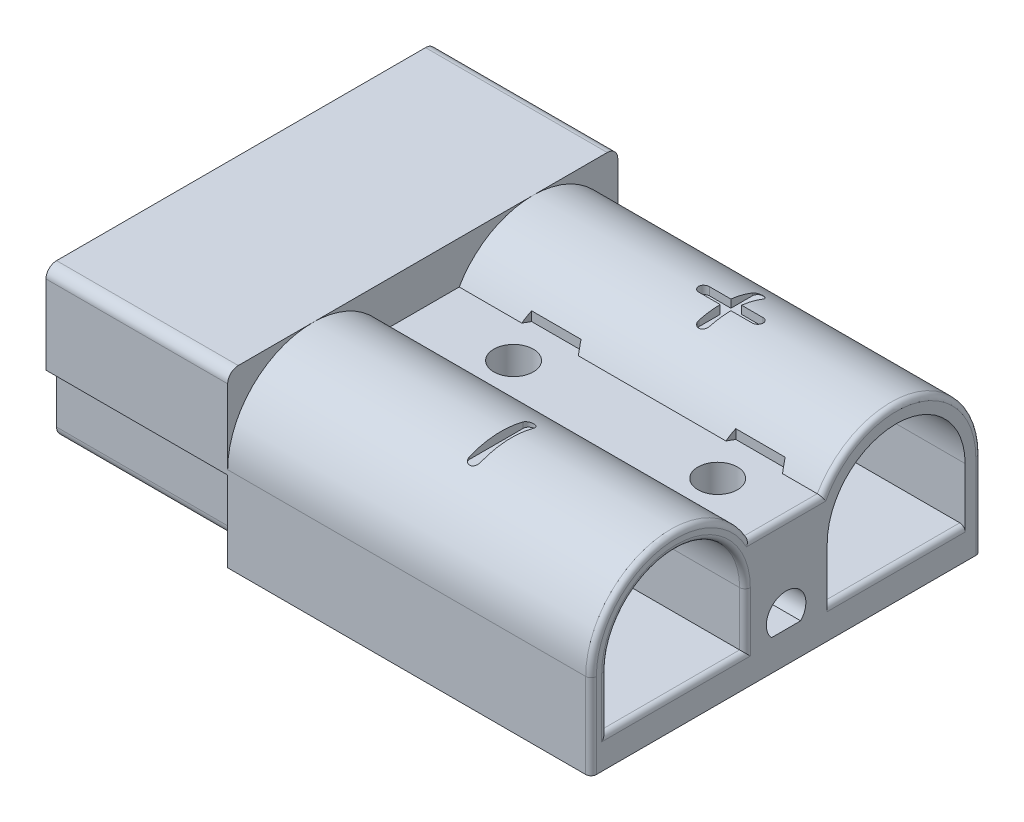
SolidWorks part; units mm, degrees
material "PC High Viscosity"
ref_plane "Front Plane" through (0, 0, 0) normal (0, 0, 1) x (1, 0, 0)
ref_plane "Top Plane" through (0, 0, 0) normal (0, 1, 0) x (1, 0, 0)
ref_plane "Right Plane" through (0, 0, 0) normal (1, 0, 0) x (0, 0, -1)
sketch "Sketch2" plane through (0, 0, 0) normal (1, 0, 0) x (0, 0, -1)
  line L0 (-10.3, -15.3774) -> (-10.3, -26.8774) construction
  line L1 (-18.25, -29.7774) -> (18.25, -29.7774)
  line L2 (-16.75, -21.8274) -> (-16.75, -26.8774)
  line L3 (0, -29.7774) -> (0, -13.8774) construction
  line L4 (10.3, -15.3774) -> (10.3, -26.8774) construction
  line L5 (3.85, -26.8774) -> (16.75, -26.8774)
  line L6 (-1.85, -13.8774) -> (-1.85, -29.7774) construction
  line L7 (1.85, -13.8774) -> (1.85, -29.7774) construction
  line L8 (-18.25, -21.8274) -> (-18.25, -29.7774)
  line L9 (18.25, -21.8274) -> (18.25, -29.7774)
  line L10 (-16.75, -26.8774) -> (-3.85, -26.8774)
  line L12 (-18.25, -21.8274) -> (-2.35, -21.8274) construction
  line L13 (16.75, -21.8274) -> (16.75, -28.2774) construction
  line L14 (2.35, -21.8274) -> (18.25, -21.8274) construction
  line L15 (-3.85, -26.8774) -> (3.85, -26.8774) construction
  line L16 (-3.4151, -17.8524) -> (3.4151, -17.8524)
  line L17 (-16.75, -21.8274) -> (-16.75, -28.2774) construction
  line L18 (-1.3638, -26.8774) -> (1.3638, -26.8774)
  line L22 (16.75, -21.8274) -> (16.75, -26.8774)
  line L32 (-3.85, -21.8274) -> (-3.85, -26.8774)
  line L33 (3.85, -21.8274) -> (3.85, -26.8774)
  line L36 (-16.75, -28.2774) -> (16.75, -28.2774) construction
  line L37 (-18.25, -29.7774) -> (18.25, -29.7774) construction
  arc A0 (-3.4151, -17.8524) -> (-18.25, -21.8274) centre (-10.3, -21.8274) ccw
  arc A1 (1.3638, -26.8774) -> (-1.3638, -26.8774) centre (0, -25.6274) ccw
  arc A5 (18.25, -21.8274) -> (3.4151, -17.8524) centre (10.3, -21.8274) ccw
  arc A7 (-3.85, -21.8274) -> (-16.75, -21.8274) centre (-10.3, -21.8274) ccw
  arc A8 (16.75, -21.8274) -> (3.85, -21.8274) centre (10.3, -21.8274) ccw
  arc A10 (18.25, -21.8274) -> (2.35, -21.8274) centre (10.3, -21.8274) ccw construction
  arc A11 (-2.35, -21.8274) -> (-18.25, -21.8274) centre (-10.3, -21.8274) ccw construction
  point P8 (0.7875, -13.9399)
  point P9 (-3.5, 15.8375)
  point P10 (-31.425, 15.8375)
  point P11 (18.25, -13.8774)
  point P12 (-31.425, -6.5)
  point P13 (0, 15.8375)
  point P15 (10.802, 3)
  point P16 (-3.5, -6.5)
  point P20 (-18.25, -13.8774)
  point P23 (-4.2255, -3.5355)
  point P24 (-2.35, -13.8774)
  point P25 (31.925, 15.8375)
  point P26 (17.4625, 15.8375)
  point P28 (-2.35, -29.7774)
  point P30 (2.35, -29.7774)
  point P43 (2.35, -13.8774)
  dimension "D3" = 1.5
  dimension "D1" = 15.9
  dimension "D2" = 36.5
extrude "Extrude1" add sketch "Sketch2" along normal blind 34
fillet "Fillet9" radius 0.5 10 edges at (34, -24.3524, 16.75) (34, -15.3774, 10.3) (34, -25.8024, -18.25) (34, -25.8024, 18.25) (34, -26.8774, -10.3) (34, -24.3524, 3.85) (34, -26.8774, 10.3) (34, -17.8524, 0) (34, -14.1483, -12.3576) (34, -14.1483, 12.3576)
ref_plane "Plane1" through (29, 0, 0) normal (1, 0, 0) x (0, 0, -1)
sketch "Sketch30" plane through (29, 0, 0) normal (1, 0, 0) x (0, 0, -1)
  line L0 (0, -17.8524) -> (0, -29.7774) construction
  line L1 (-3.4151, -17.8524) -> (3.4151, -17.8524) construction
  line L3 (-18.25, -21.8274) -> (18.25, -21.8274) construction
ref_plane "Plane3" through (29, 0, 0) normal (1, 0, 0) x (0, 0, -1)
ref_plane "Plane4" through (0, 0, 0) normal (0, 0, 1) x (1, 0, 0)
ref_plane "Plane7" through (0, 0, 0) normal (-1, 0, 0) x (0, 0, 1)
sketch "Sketch24" plane through (0, 0, 0) normal (-1, 0, 0) x (0, 0, 1)
  line L0 (0, -29.7774) -> (0, -13.8774) construction
  line L2 (-17.2613, -22.3827) -> (-16.2725, -22.3827) construction
  line L3 (-17.2613, -27.3623) -> (-17.2613, -22.3827)
  line L4 (-0.4944, -14.8661) -> (-17.2613, -14.8661) construction
  line L5 (-17.2613, -22.2591) -> (-17.2613, -22.3827)
  line L6 (0.4944, -18.8211) -> (0.9887, -18.8211) construction
  line L7 (17.2613, -22.2591) -> (18.25, -22.2591)
  line L8 (0.9887, -18.8211) -> (0.9887, -19.8098) construction
  line L9 (17.2613, -27.3623) -> (17.2613, -22.3827)
  line L10 (-0.9887, -18.8211) -> (-0.9887, -19.8098) construction
  line L11 (-16.2725, -23.3714) -> (-16.2725, -22.3827) construction
  line L12 (-0.9887, -24.3602) -> (0.9887, -24.3602) construction
  line L13 (16.2725, -23.3714) -> (16.2725, -22.3827) construction
  line L14 (-17.2613, -22.2591) -> (-17.2613, -14.8661) construction
  line L15 (-16.2725, -28.351) -> (16.2725, -28.351)
  line L16 (0.4944, -14.8661) -> (0.4944, -18.8211) construction
  line L17 (18.25, -22.2591) -> (18.25, -14.8661)
  line L18 (0, -13.8774) -> (0, -22.3827) construction
  line L19 (16.2725, -23.3714) -> (-16.2725, -23.3714) construction
  line L20 (0, -24.8545) -> (0, -29.635) construction
  line L21 (17.2613, -13.8774) -> (-17.2613, -13.8774)
  line L22 (17.2613, -22.3827) -> (16.2725, -22.3827) construction
  line L23 (17.2613, -22.2591) -> (17.2613, -14.8661) construction
  line L24 (-18.25, -22.2591) -> (-17.2613, -22.2591)
  line L25 (-0.9887, -18.8211) -> (-0.4944, -18.8211) construction
  line L26 (16.2725, -22.3827) -> (-16.2725, -22.3827) construction
  line L27 (-0.4944, -14.8661) -> (-0.4944, -18.8211) construction
  line L28 (-18.25, -22.2591) -> (-18.25, -14.8661)
  line L29 (-0.9887, -19.8098) -> (0.9887, -19.8098) construction
  line L30 (-0.9887, -24.3602) -> (-0.9887, -28.3623) construction
  line L31 (1.1944, -14.8661) -> (17.2613, -14.8661) construction
  line L32 (17.2613, -22.2591) -> (17.2613, -22.3827)
  line L34 (0.9887, -24.3602) -> (0.9887, -28.3623) construction
  arc A0 (1.9775, -28.351) -> (0.9887, -27.3623) centre (1.9775, -27.3623) cw construction
  arc A1 (-17.2613, -13.8774) -> (-18.25, -14.8661) centre (-17.2613, -14.8661) ccw
  arc A2 (-16.2725, -28.351) -> (-17.2613, -27.3623) centre (-16.2725, -27.3623) cw
  arc A3 (18.25, -14.8661) -> (17.2613, -13.8774) centre (17.2613, -14.8661) ccw
  arc A4 (-0.9887, -27.3623) -> (-1.9775, -28.351) centre (-1.9775, -27.3623) cw construction
  arc A5 (17.2613, -27.3623) -> (16.2725, -28.351) centre (16.2725, -27.3623) cw
  point P9 (-33.5, 31.3)
  point P10 (33.5, 31.3)
  point P13 (-31.5, 2)
  point P16 (31.5, 2)
  point P22 (31.5, 4)
  point P23 (31.5, 16.0955)
  point P30 (-31.5, 4)
  point P36 (-31.5, 16.0955)
extrude "Extrude8" add sketch "Sketch24" along normal blind 2
ref_plane "Plane8" through (-2, 0, 0) normal (-1, 0, 0) x (0, 0, 1)
sketch "Sketch25" plane through (-2, 0, 0) normal (-1, 0, 0) x (0, 0, 1)
  line L0 (-17.2613, -13.8774) -> (17.2613, -13.8774)
  line L1 (-18.25, -14.8661) -> (-18.25, -22.2591)
  line L2 (-18.25, -22.2591) -> (-17.2613, -22.2591)
  line L3 (-17.2613, -22.2591) -> (-17.2613, -14.8661)
  line L4 (-17.2613, -14.8661) -> (-0.4944, -14.8661)
  line L5 (-0.4944, -14.8661) -> (-0.4944, -18.8211)
  line L6 (-0.4944, -18.8211) -> (-0.9887, -18.8211)
  line L7 (-0.9887, -18.8211) -> (-0.9887, -19.8098)
  line L8 (-0.9887, -19.8098) -> (0.9887, -19.8098)
  line L9 (0.9887, -19.8098) -> (0.9887, -18.8211)
  line L10 (0.9887, -18.8211) -> (0.4944, -18.8211)
  line L11 (0.4944, -18.8211) -> (0.4944, -14.8661)
  line L12 (0.4944, -14.8661) -> (17.2613, -14.8661)
  line L13 (17.2613, -14.8661) -> (17.2613, -22.2591)
  line L14 (17.2613, -22.2591) -> (18.25, -22.2591)
  line L15 (18.25, -22.2591) -> (18.25, -14.8661)
  line L16 (-17.2613, -27.3623) -> (-17.2613, -22.3827)
  line L17 (-17.2613, -22.3827) -> (-16.2725, -22.3827)
  line L18 (-16.2725, -22.3827) -> (-16.2725, -23.3714)
  line L19 (-16.2725, -23.3714) -> (16.2725, -23.3714)
  line L20 (16.2725, -23.3714) -> (16.2725, -22.3827)
  line L21 (16.2725, -22.3827) -> (17.2613, -22.3827)
  line L22 (17.2613, -22.3827) -> (17.2613, -27.3623)
  line L23 (-16.2725, -28.351) -> (-1.9775, -28.351)
  line L24 (1.9775, -28.351) -> (16.2725, -28.351)
  line L25 (-0.9887, -27.3623) -> (-0.9887, -24.3602)
  line L26 (-0.9887, -24.3602) -> (0.9887, -24.3602)
  line L27 (0.9887, -24.3602) -> (0.9887, -27.3623)
  arc A0 (-18.25, -14.8661) -> (-17.2613, -13.8774) centre (-17.2613, -14.8661) cw
  arc A1 (17.2613, -13.8774) -> (18.25, -14.8661) centre (17.2613, -14.8661) cw
  arc A2 (-17.2613, -27.3623) -> (-16.2725, -28.351) centre (-16.2725, -27.3623) ccw
  arc A3 (-1.9775, -28.351) -> (-0.9887, -27.3623) centre (-1.9775, -27.3623) ccw
  arc A4 (0.9887, -27.3623) -> (1.9775, -28.351) centre (1.9775, -27.3623) ccw
  arc A5 (16.2725, -28.351) -> (17.2613, -27.3623) centre (16.2725, -27.3623) ccw
  point P9 (-33.5, 31.3)
  point P10 (33.5, 31.3)
  point P13 (-31.5, 2)
  point P16 (31.5, 2)
  point P22 (31.5, 4)
  point P23 (31.5, 16.0955)
  point P30 (-31.5, 4)
  point P36 (-31.5, 16.0955)
extrude "Extrude9" add sketch "Sketch25" along normal blind 15
ref_plane "Plane5" through (0, -17.8524, 0) normal (0, 1, 0) x (-1, 0, 0)
sketch "Sketch22" plane through (0, -17.8524, 0) normal (0, 1, 0) x (-1, 0, 0)
  line L0 (-34, 0) -> (0, 0) construction
  line L2 (-34, -3.7101) -> (-34, 3.7101) construction
  circle A0 centre (-27.6, 0) radius 1.85
  circle A1 centre (-8.5, 0) radius 1.85
  dimension "D1" = 3.7
  dimension "D3" = 19.1
  dimension "D2" = 6.4
extrude "Extrude5" cut sketch "Sketch22" against normal blind 32.7
ref_plane "Plane6" through (0, -17.8524, 0) normal (0, 1, 0) x (-1, 0, 0)
sketch "Sketch23" plane through (0, -17.8524, 0) normal (0, 1, 0) x (-1, 0, 0)
  line L0 (-29.9094, 4) -> (-32.2188, 0)
  line L7 (-22.9812, 0) -> (-25.2906, 4)
  line L8 (-32.2188, 0) -> (-29.9094, -4)
  line L9 (-29.9094, -4) -> (-25.2906, -4)
  line L10 (-25.2906, 4) -> (-29.9094, 4)
  line L11 (-25.2906, -4) -> (-22.9812, 0)
  line L12 (-10.8094, 4) -> (-13.1188, 0)
  line L13 (-3.8812, 0) -> (-6.1906, 4)
  line L14 (-13.1188, 0) -> (-10.8094, -4)
  line L15 (-10.8094, -4) -> (-6.1906, -4)
  line L16 (-6.1906, 4) -> (-10.8094, 4)
  line L17 (-6.1906, -4) -> (-3.8812, 0)
  circle A1 centre (-27.6, 0) radius 4 construction
  circle A2 centre (-8.5, 0) radius 4 construction
  dimension "D2" = 8
  dimension "D3" = 8
extrude "Extrude6" cut sketch "Sketch23" along normal blind 2.7
ref_plane "Plane9" through (0, -13.8774, 0) normal (0, 1, 0) x (-1, 0, 0)
ref_plane "Plane12" through (0, -13.8774, 0) normal (0, 1, 0) x (-1, 0, 0)
sketch "Sketch29" plane through (0, -13.8774, 0) normal (0, 1, 0) x (-1, 0, 0)
  line L3 (-18.105, -8.23) -> (-18.105, -13.23) construction
  line L4 (-17.605, -11.23) -> (-15.605, -11.23)
  line L6 (-17.605, -10.23) -> (-15.605, -10.23)
  line L7 (-18.605, -11.23) -> (-18.605, -13.23)
  line L8 (-17.605, -11.23) -> (-17.605, -13.23)
  line L9 (-18.125, 13.23) -> (-18.125, 8.23) construction
  line L10 (-17.625, 13.23) -> (-17.625, 8.23)
  line L11 (-18.625, 13.23) -> (-18.625, 8.23)
  line L16 (-18.605, -8.23) -> (-18.605, -10.23)
  line L17 (-20.605, -10.73) -> (-15.605, -10.73) construction
  line L18 (-20.605, -10.23) -> (-18.605, -10.23)
  line L19 (-17.605, -8.23) -> (-17.605, -10.23)
  line L20 (-20.605, -11.23) -> (-18.605, -11.23)
  arc A0 (-17.605, -8.23) -> (-18.605, -8.23) centre (-18.105, -8.23) ccw
  arc A1 (-18.605, -13.23) -> (-17.605, -13.23) centre (-18.105, -13.23) ccw
  arc A4 (-17.625, 13.23) -> (-18.625, 13.23) centre (-18.125, 13.23) ccw
  arc A5 (-18.625, 8.23) -> (-17.625, 8.23) centre (-18.125, 8.23) ccw
  arc A6 (-15.605, -11.23) -> (-15.605, -10.23) centre (-15.605, -10.73) ccw
  arc A7 (-20.605, -10.23) -> (-20.605, -11.23) centre (-20.605, -10.73) ccw
  point P14 (-18.105, -10.73)
  point P21 (-18.125, 10.73)
  point P32 (-18.105, -10.73)
extrude "Extrude13" cut sketch "Sketch29" against normal blind 0.8
ref_plane "Plane14" through (0, -28.351, 0) normal (0, -1, 0) x (1, 0, 0)
sketch "Sketch32" plane through (0, -28.351, 0) normal (0, -1, 0) x (1, 0, 0)
  line L0 (-8.5, 17.2613) -> (-8.5, -17.2613) construction
  line L1 (-17, 17.2613) -> (0, 17.2613) construction
  line L2 (-17, -17.2613) -> (0, -17.2613) construction
  line L3 (-17, 9.125) -> (0, 9.125) construction
  line L4 (-17, 1.9775) -> (-17, 16.2725) construction
  line L5 (0, -16.2725) -> (0, 16.2725) construction
  line L6 (-17, -9.125) -> (0, -9.125) construction
  line L7 (-17, -16.2725) -> (-17, -1.9775) construction
  line L8 (0, 18.25) -> (0, -18.25) construction
  line L9 (-8.5, 13.125) -> (-8.5, 5.125) construction
  line L12 (-9.3, -9.925) -> (-9.3, -13.125)
  line L13 (-7.7, 13.125) -> (-7.7, 5.125)
  line L14 (-9.3, -5.125) -> (-9.3, -8.325)
  line L15 (-9.3, 13.125) -> (-9.3, 5.125)
  line L26 (-7.7, -5.125) -> (-7.7, -8.325)
  line L27 (-12.5, -9.925) -> (-9.3, -9.925)
  line L28 (-7.7, -9.925) -> (-7.7, -13.125)
  line L29 (-8.5, -5.125) -> (-8.5, -13.125) construction
  line L30 (-7.7, -8.325) -> (-4.5, -8.325)
  line L31 (-7.7, -9.925) -> (-4.5, -9.925)
  line L32 (-12.5, -9.125) -> (-4.5, -9.125) construction
  line L33 (-12.5, -8.325) -> (-9.3, -8.325)
  arc A0 (-7.7, 13.125) -> (-9.3, 13.125) centre (-8.5, 13.125) ccw
  arc A1 (-9.3, 5.125) -> (-7.7, 5.125) centre (-8.5, 5.125) ccw
  arc A2 (-4.5, -9.925) -> (-4.5, -8.325) centre (-4.5, -9.125) ccw
  arc A3 (-9.3, -13.125) -> (-7.7, -13.125) centre (-8.5, -13.125) ccw
  arc A8 (-12.5, -8.325) -> (-12.5, -9.925) centre (-12.5, -9.125) ccw
  arc A9 (-7.7, -5.125) -> (-9.3, -5.125) centre (-8.5, -5.125) ccw
  point P24 (-8.5, 9.125)
  point P53 (-8.5, -9.125)
  point P60 (-8.5, -9.125)
extrude "Extrude14" cut sketch "Sketch32" against normal blind 0.25
